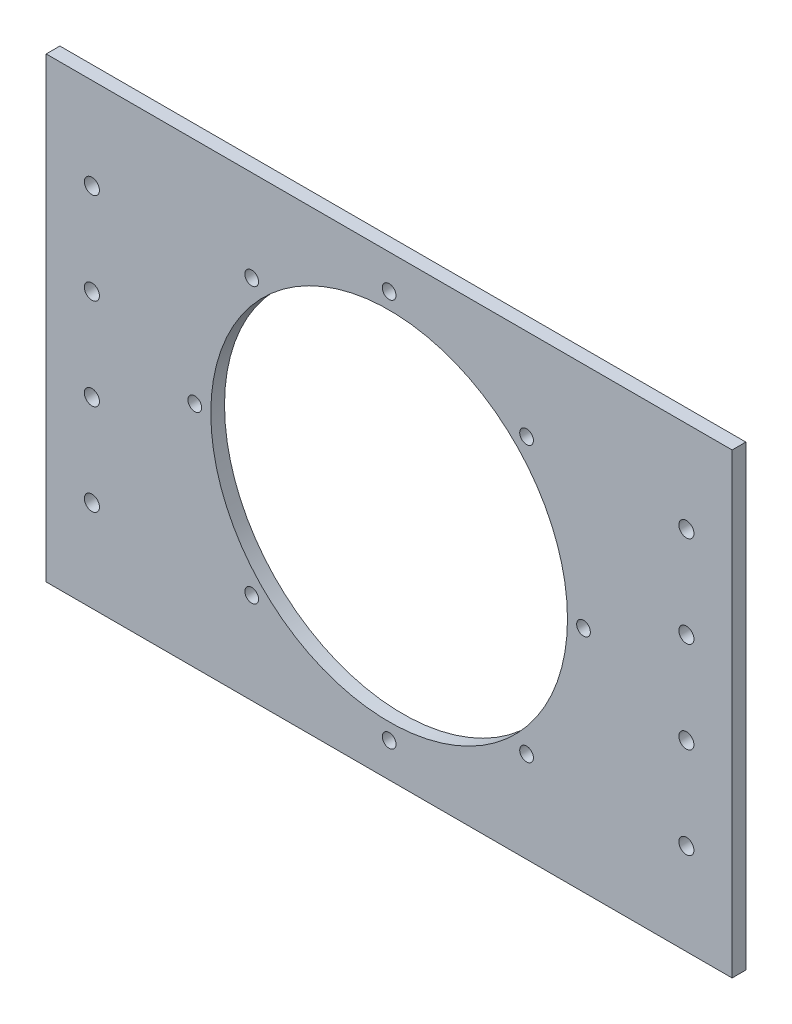
SolidWorks part; units mm, degrees
ref_plane "前视基准面" through (0, 0, 0) normal (0, 0, 1) x (1, 0, 0)
ref_plane "上视基准面" through (0, 0, 0) normal (0, 1, 0) x (1, 0, 0)
ref_plane "右视基准面" through (0, 0, 0) normal (1, 0, 0) x (0, 0, -1)
other "Configuration Table"
sketch "草图1" plane through (0, 0, 0) normal (0, 0, 1) x (1, 0, 0)
  line L0 (0, 0) -> (0, 90.0014) construction
  line L5 (-75, 50) -> (75, 50)
  line L6 (-75, 50) -> (-75, -50)
  line L7 (-75, -50) -> (75, -50)
  line L8 (75, 50) -> (75, -50)
  line L9 (-75, 50) -> (75, -50) construction
  line L10 (-75, -50) -> (75, 50) construction
  line L11 (-65, 50) -> (-65, -50) construction
  line L12 (65, 50) -> (65, -50) construction
  circle A10 centre (0, 0) radius 39
  circle A11 centre (0, 0) radius 42.5 construction
  circle A13 centre (42.5, 0) radius 1.5
  circle A14 centre (30.052, -30.052) radius 1.5
  circle A15 centre (0, -42.5) radius 1.5
  circle A16 centre (-30.052, -30.052) radius 1.5
  circle A17 centre (-42.5, 0) radius 1.5
  circle A18 centre (-30.052, 30.052) radius 1.5
  circle A19 centre (0, 42.5) radius 1.5
  circle A20 centre (30.052, 30.052) radius 1.5
  circle A21 centre (-65, 30) radius 1.65
  circle A22 centre (-65, 10) radius 1.65
  circle A23 centre (-65, -10) radius 1.65
  circle A24 centre (-65, -30) radius 1.65
  circle A25 centre (65, -30) radius 1.65
  circle A26 centre (65, -10) radius 1.65
  circle A27 centre (65, 10) radius 1.65
  circle A28 centre (65, 30) radius 1.65
  circle A29 centre (0, 0) radius 44.5 construction
  circle A30 centre (0, 0) radius 44.5 construction
  point P22 (0, 0)
  dimension "D2" = 78
  dimension "D4" = 3
  dimension "D3" = 85
  dimension "D10" = 3.3
  dimension "D11" = 3.3
  dimension "D12" = 3.3
  dimension "D13" = 3.3
  dimension "D17" = 89
  dimension "D18" = 89
  dimension "D6" = 100
  dimension "D7" = 150
  dimension "D8" = 10
  dimension "D9" = 20
  dimension "D14" = 20
  dimension "D15" = 20
  dimension "D16" = 20
  dimension "D5" = 8
extrude "凸台-拉伸1" add sketch "草图1" along normal blind 3
